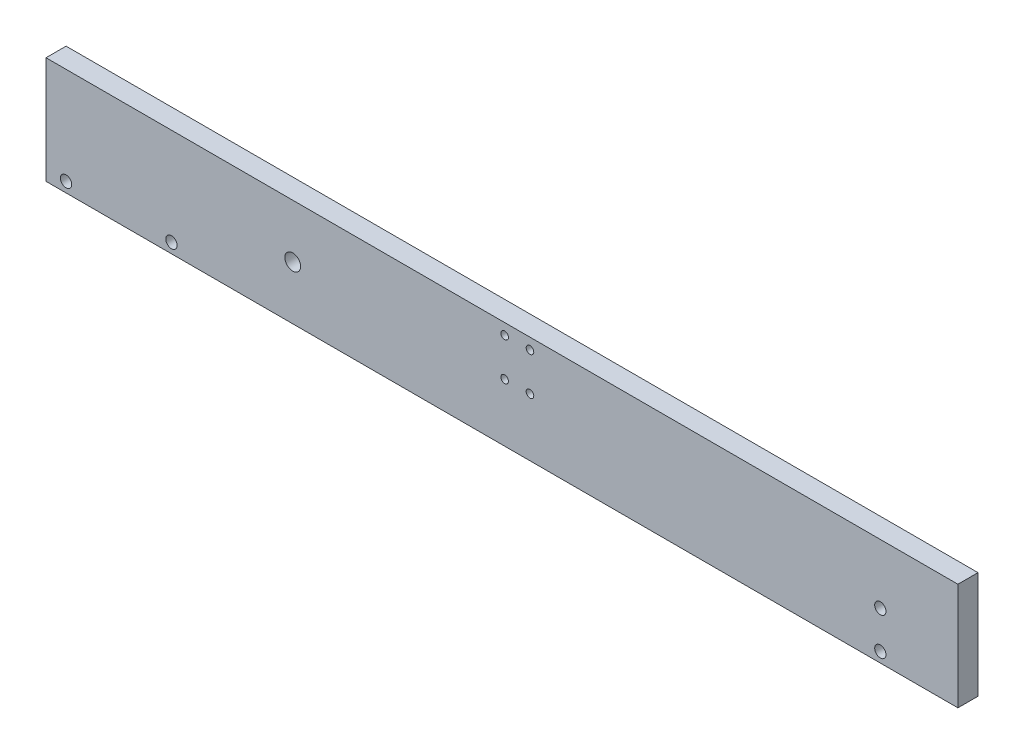
SolidWorks part; units mm, degrees
ref_plane "Front Plane" through (0, 0, 0) normal (0, 0, 1) x (1, 0, 0)
ref_plane "Top Plane" through (0, 0, 0) normal (0, 1, 0) x (1, 0, 0)
ref_plane "Right Plane" through (0, 0, 0) normal (1, 0, 0) x (0, 0, -1)
sketch "Sketch1" plane through (0, 0, 0) normal (0, 0, 1) x (1, 0, 0)
  line B0 (0, 0) -> (-288.29, 0)
  line B1 (0, 0) -> (0, 33.85)
  line B2 (0, 33.85) -> (-288.29, 33.85)
  line B3 (-288.29, 33.85) -> (-288.29, 0)
  circle B4 centre (-210.29, 16.925) radius 2.5
  circle B5 centre (-135.29, 18.35) radius 1.2
  circle B6 centre (-135.29, 30.35) radius 1.2
  circle B7 centre (-143.29, 18.35) radius 1.2
  circle B8 centre (-143.29, 30.35) radius 1.2
  circle B9 centre (-248.64, 3.175) radius 1.7859
  circle B10 centre (-281.94, 3.175) radius 1.7859
  circle B11 centre (-24.525, 15.025) radius 1.7859
  circle B12 centre (-24.525, 3.175) radius 1.7859
sketch_block_instance "Left_Side_IC-1"
sketch_block "Left_Side_IC" parameters "D1"=3.5719
extrude "Boss-Extrude1" add sketch "Sketch1" along normal blind 6.35
